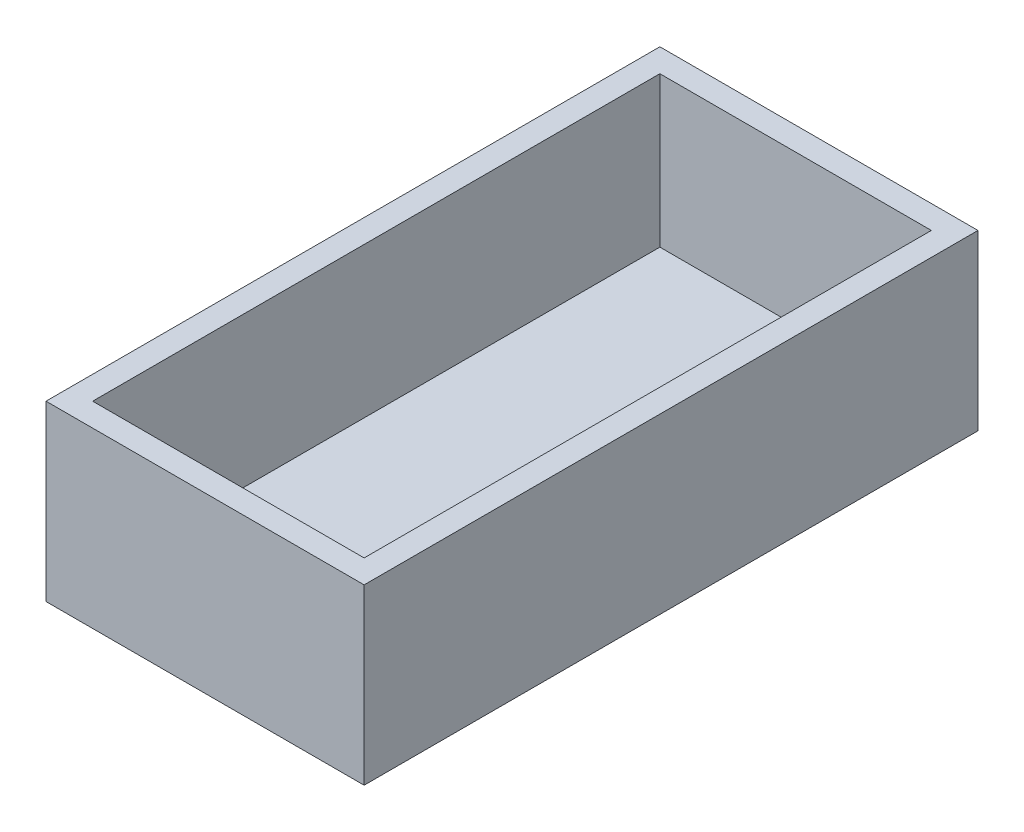
SolidWorks part; units mm, degrees
ref_plane "Front Plane" through (0, 0, 0) normal (0, 0, 1) x (1, 0, 0)
ref_plane "Top Plane" through (0, 0, 0) normal (0, 1, 0) x (1, 0, 0)
ref_plane "Right Plane" through (0, 0, 0) normal (1, 0, 0) x (0, 0, -1)
sketch "Sketch3" plane through (0, 0, 0) normal (0, 1, 0) x (1, 0, 0)
  line L0 (20.066, -41.783) -> (20.066, 41.783)
  line L5 (16.764, -25.781) -> (-16.764, 25.781) construction
  line L6 (16.764, 25.781) -> (-16.764, -25.781) construction
  line L7 (20.066, 41.783) -> (-23.241, 41.783)
  line L8 (-23.241, -41.783) -> (-23.241, 41.783)
  line L9 (20.066, -41.783) -> (-23.241, -41.783)
  point P0 (0, 0)
  dimension "D1" = 83.566
  dimension "D2" = 43.307
extrude "Boss-Extrude1" add sketch "Sketch3" along normal blind 23.622
shell "Shell2" thickness 3.175
